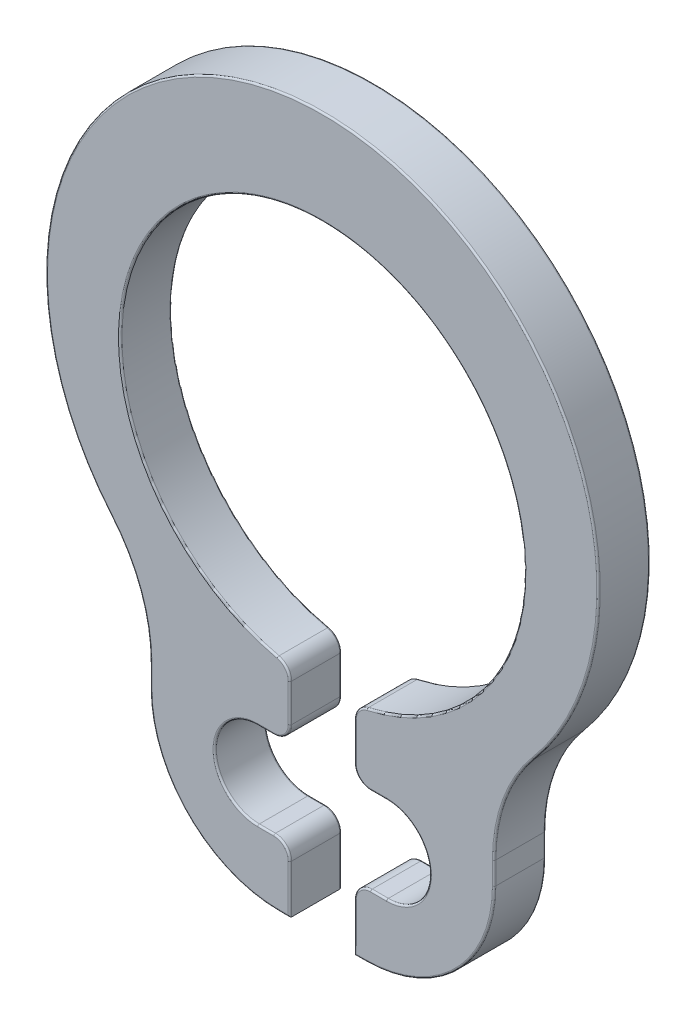
SolidWorks part; units mm, degrees
ref_plane "Front Plane" through (0, 0, 0) normal (0, 0, 1) x (1, 0, 0)
ref_plane "Top Plane" through (0, 0, 0) normal (0, 1, 0) x (1, 0, 0)
ref_plane "Right Plane" through (0, 0, 0) normal (1, 0, 0) x (0, 0, -1)
sketch "Sketch1" plane through (0, 0, 0) normal (0, 0, 1) x (1, 0, 0)
  line L0 (0, 4.15) -> (0, -4.15) construction
  line L1 (-0.75, -2.9) -> (0.75, -2.9) construction
  line L2 (-0.75, -2.4) -> (0.75, -2.4)
  line L3 (-0.75, -3.4) -> (0.75, -3.4)
  line L4 (1.25, -2.9) -> (2, -2.9) construction
  line L5 (0, -1.65) -> (0, -2.4) construction
  circle A0 centre (0, 0.7) radius 2.35
  arc A3 (-0.75, -2.4) -> (-0.75, -3.4) centre (-0.75, -2.9) ccw
  arc A4 (0.75, -3.4) -> (0.75, -2.4) centre (0.75, -2.9) ccw
  circle A5 centre (0, 0.935) radius 3.215 construction
  circle A6 centre (0, 0.7) radius 2.5 construction
  circle A7 centre (0, 0.7) radius 2.4 construction
  point P6 (0, 3.05)
  point P7 (0, -1.65)
  point P10 (0, -2.9)
  dimension "For OD" = 5
  dimension "ID" = 4.7
  dimension "Band Width" = 1.1
  dimension "Tap Height" = 2.5
  dimension "Tap ID" = 1
  dimension "D3" = 1.25
  dimension "Tap Width Ref" = 4
  dimension "D1" = 0.235
sketch "Sketch2" plane through (0, 0, 0) normal (1, 0, 0) x (0, 0, -1)
  line L0 (-0.3, 4.15) -> (0.3, 4.15) construction
  line L1 (0, 5.55) -> (0, -4.15) construction
  line L2 (0, 4.15) -> (0, -4.15) construction
  line L3 (-0.35, 5.55) -> (0.35, 5.55) construction
  line L4 (-0.35, -4.15) -> (0.35, -4.15) construction
  dimension "Thickness" = 0.6
  dimension "For Groove Width" = 0.7
sketch "Sketch3" plane through (0, 0, 0) normal (0, 0, 1) x (1, 0, 0)
  line L0 (-0.75, -3.4) -> (0.75, -3.4) construction
  line L1 (-0.75, -2.4) -> (0.75, -2.4) construction
  line L2 (-0.75, -3.4) -> (0.75, -3.4)
  line L3 (-0.75, -2.4) -> (0.75, -2.4)
  line L4 (2, -2.3885) -> (2, -2.65)
  line L5 (-0.5, -4.15) -> (0.5, -4.15)
  line L6 (-2, -2.3885) -> (-2, -2.65)
  line L7 (-1.25, -2.9) -> (-2, -2.9) construction
  line L8 (1.25, -2.9) -> (2, -2.9) construction
  arc A0 (-0.75, -2.4) -> (-0.75, -3.4) centre (-0.75, -2.9) ccw construction
  arc A1 (0.75, -3.4) -> (0.75, -2.4) centre (0.75, -2.9) ccw construction
  arc A2 (-0.75, -2.4) -> (-0.75, -3.4) centre (-0.75, -2.9) ccw
  arc A3 (0.75, -3.4) -> (0.75, -2.4) centre (0.75, -2.9) ccw
  circle A4 centre (0, 0.7) radius 2.35 construction
  circle A5 centre (0, 0.7) radius 2.35
  arc A6 (-2.457, -1.1385) -> (2.457, -1.1385) centre (0, 0.935) cw
  arc A8 (2.457, -1.1385) -> (2, -2.3885) centre (3.9381, -2.3885) ccw
  arc A9 (2, -2.65) -> (0.5, -4.15) centre (0.5, -2.65) cw
  arc A10 (-2.457, -1.1385) -> (-2, -2.3885) centre (-3.9381, -2.3885) cw
  arc A11 (-2, -2.65) -> (-0.5, -4.15) centre (-0.5, -2.65) ccw
  circle A12 centre (0, 0.935) radius 3.215 construction
  dimension "D1" = 1.25
  dimension "D2" = 1.5
  dimension "D3" = 0.75
extrude "Boss-Extrude1" add sketch "Sketch3" along normal mid plane 0.6
sketch "Sketch4" plane through (0, 0, 0) normal (0, 0, 1) x (1, 0, 0)
  line L0 (0, 0.7) -> (0, -4.15)
extrude "Cut-Extrude-Thin1" cut sketch "Sketch4" against normal through all both and the other way through all thin thin type mid plane wall 0.75
fillet "Fillet2" radius 0.1875 6 edges at (0.375, -3.4, 0) (-0.375, -3.4, 0) (0.375, -2.4, 0) (0.375, -1.6199, 0) (-0.375, -2.4, 0) (-0.375, -1.6199, 0)
fillet "Fillet1" radius 0.02 52 edges at (-0.6562, -3.4, -0.3) (-1.25, -2.9, -0.3) (-0.6562, -2.4, -0.3) (0, 3.05, -0.3) (0.6562, -2.4, -0.3) (1.25, -2.9, -0.3) (0.6562, -3.4, -0.3) (0.375, -3.8688, -0.3) (0.4375, -4.15, -0.3) (1.5607, -3.7107, -0.3) (2, -2.5193, -0.3) (2.1178, -1.7231, -0.3) (0, 4.15, -0.3) (-2.1178, -1.7231, -0.3) (-2, -2.5193, -0.3) (-1.5607, -3.7107, -0.3) (-0.4375, -4.15, -0.3) (-0.375, -3.8688, -0.3) (-1.5607, -3.7107, 0.3) (-2, -2.5193, 0.3) (-2.1178, -1.7231, 0.3) (0, 4.15, 0.3) (2.1178, -1.7231, 0.3) (2, -2.5193, 0.3) (1.5607, -3.7107, 0.3) (0.4375, -4.15, 0.3) (0.375, -3.8688, 0.3) (0.6562, -3.4, 0.3) (1.25, -2.9, 0.3) (0.6562, -2.4, 0.3) (0, 3.05, 0.3) (-0.6562, -2.4, 0.3) (-1.25, -2.9, 0.3) (-0.6562, -3.4, 0.3) (-0.375, -3.8688, 0.3) (-0.4375, -4.15, 0.3) (-0.4299, -3.4549, -0.3) (-0.4299, -2.3451, -0.3) (-0.375, -1.9934, -0.3) (-0.416, -1.6574, -0.3) (0.416, -1.6574, -0.3) (0.375, -1.9934, -0.3) (0.4299, -2.3451, -0.3) (0.4299, -3.4549, -0.3) (0.4299, -2.3451, 0.3) (0.375, -1.9934, 0.3) (0.416, -1.6574, 0.3) (-0.416, -1.6574, 0.3) (-0.375, -1.9934, 0.3) (-0.4299, -2.3451, 0.3) (-0.4299, -3.4549, 0.3) (0.4299, -3.4549, 0.3)
equation "\"D3@Sketch1\"=\"Tap Height@Sketch1\"*0.5"
equation "\"D1@Sketch3\"=\"Tap Height@Sketch1\"*0.5"
equation "\"D2@Sketch3\"=\"Tap Height@Sketch1\"*0.6"
equation "\"D1@Boss-Extrude1\" = \"Thickness@Sketch2\""
equation "\"D1@Sketch1\"= \"ID@Sketch1\" * 0.05"
equation "\"D1@Fillet2\"=\"D3@Sketch3\"*0.25"
